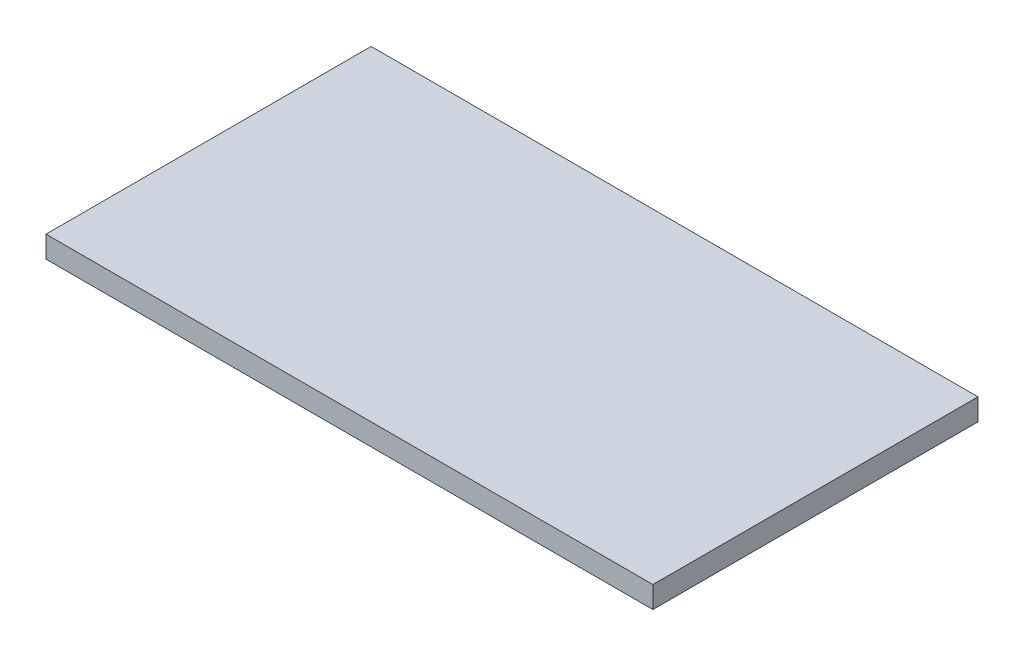
SolidWorks part; units mm, degrees
ref_plane "Front Plane" through (0, 0, 0) normal (0, 0, 1) x (1, 0, 0)
ref_plane "Top Plane" through (0, 0, 0) normal (0, 1, 0) x (1, 0, 0)
ref_plane "Right Plane" through (0, 0, 0) normal (1, 0, 0) x (0, 0, -1)
sketch "Sketch1" plane through (0, 0, 0) normal (0, 1, 0) x (1, 0, 0)
  line L1 (0, 0) -> (1422.4, 0)
  line L2 (0, 0) -> (0, 762)
  line L3 (0, 762) -> (1422.4, 762)
  line L4 (1422.4, 0) -> (1422.4, 762)
  dimension "D1" = 762
  dimension "D2" = 1422.4
extrude "Boss-Extrude1" add sketch "Sketch1" along normal blind 50.8
